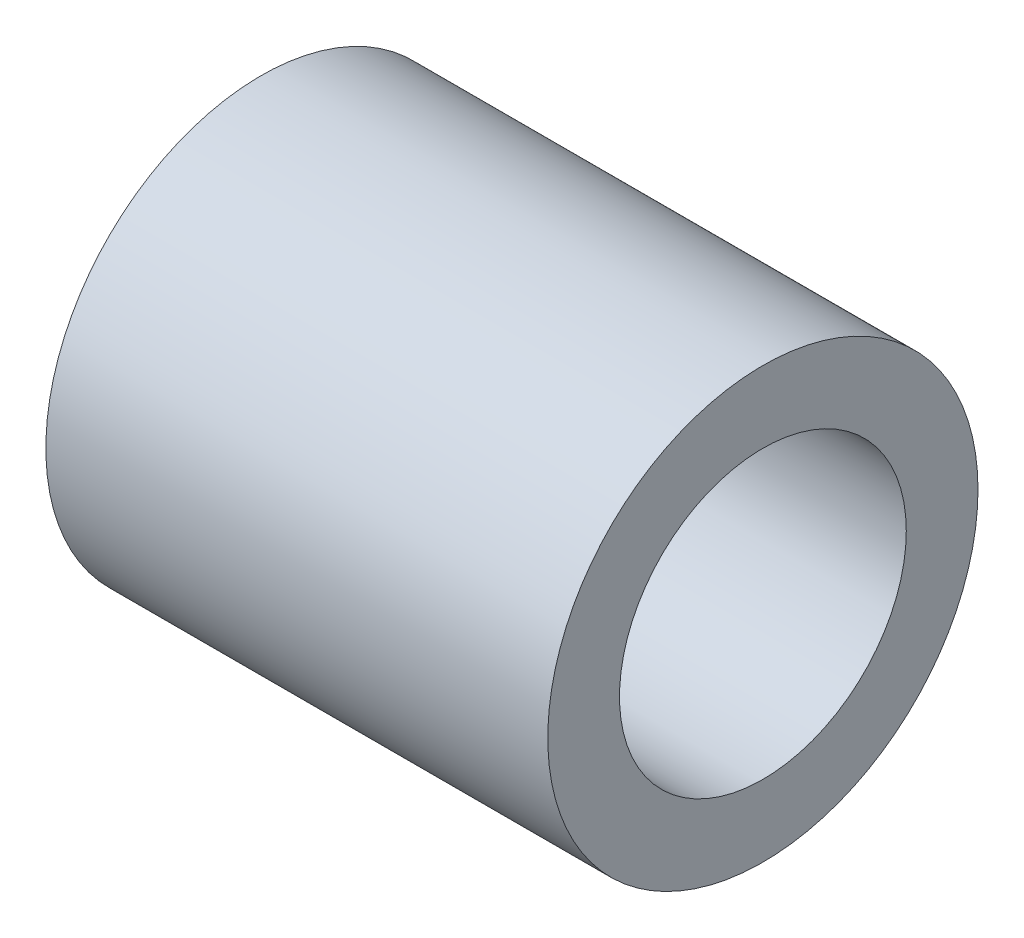
SolidWorks part; units mm, degrees
ref_plane "Alzado" through (0, 0, 0) normal (0, 0, 1) x (1, 0, 0)
ref_plane "Planta" through (0, 0, 0) normal (0, 1, 0) x (1, 0, 0)
ref_plane "Vista lateral" through (0, 0, 0) normal (1, 0, 0) x (0, 0, -1)
sketch "Croquis1" plane through (0, 0, 0) normal (1, 0, 0) x (0, 0, -1)
  circle A0 centre (0, 0) radius 0.25
  circle A1 centre (0, 0) radius 0.375
  dimension "D1" = 0.5
  dimension "D2" = 0.75
extrude "Saliente-Extruir1" add sketch "Croquis1" along normal blind 0.875
